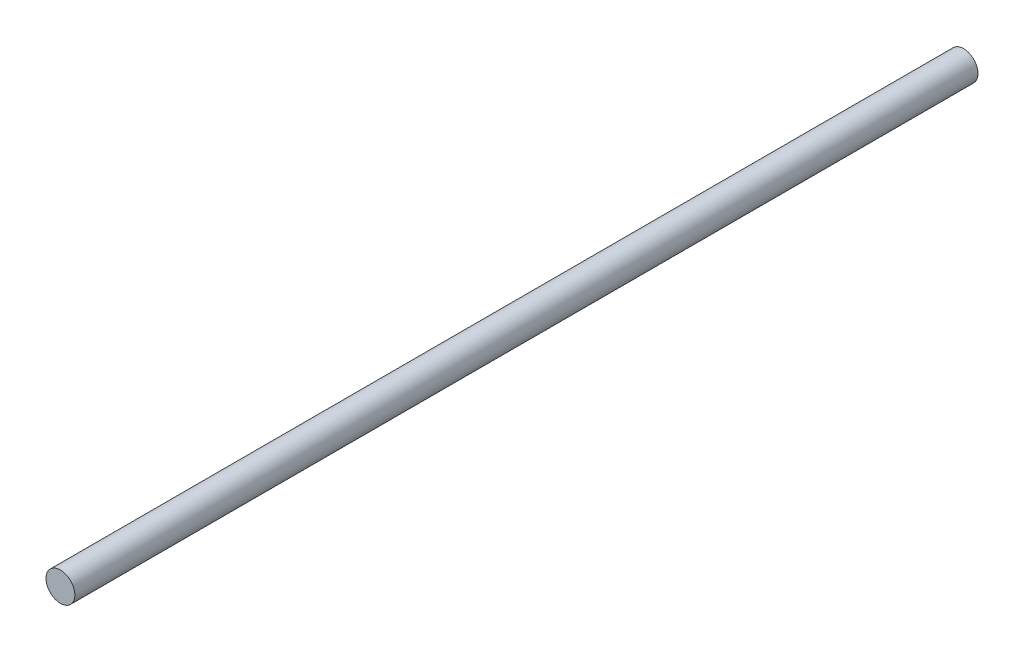
SolidWorks part; units mm, degrees
ref_plane "Front Plane" through (0, 0, 0) normal (0, 0, 1) x (1, 0, 0)
ref_plane "Top Plane" through (0, 0, 0) normal (0, 1, 0) x (1, 0, 0)
ref_plane "Right Plane" through (0, 0, 0) normal (1, 0, 0) x (0, 0, -1)
sketch "Sketch1" plane through (0, 0, 0) normal (0, 0, 1) x (1, 0, 0)
  circle A0 centre (0, 0) radius 0.4064
  dimension "D1" = 0.8128
extrude "Boss-Extrude1" add sketch "Sketch1" against normal blind 25.4
